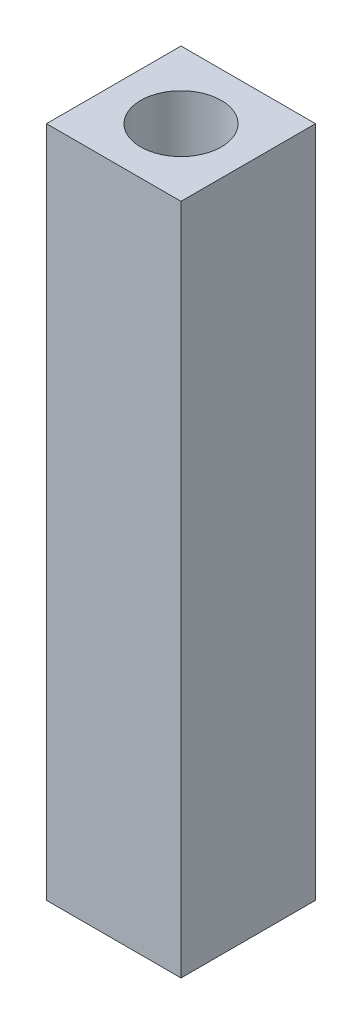
SolidWorks part; units mm, degrees
ref_plane "Front Plane" through (0, 0, 0) normal (0, 0, 1) x (1, 0, 0)
ref_plane "Top Plane" through (0, 0, 0) normal (0, 1, 0) x (1, 0, 0)
ref_plane "Right Plane" through (0, 0, 0) normal (1, 0, 0) x (0, 0, -1)
sketch "Sketch1" plane through (0, 0, 0) normal (0, 1, 0) x (1, 0, 0)
  line L1 (-5, 5) -> (5, 5)
  line L2 (-5, 5) -> (-5, -5)
  line L3 (-5, -5) -> (5, -5)
  line L4 (5, 5) -> (5, -5)
  line L5 (-5, 5) -> (5, -5) construction
  line L6 (-5, -5) -> (5, 5) construction
  dimension "D1" = 5
  dimension "D2" = 10
  dimension "D3" = 10
  dimension "D4" = 5
extrude "Boss-Extrude1" add sketch "Sketch1" along normal blind 50
sketch "Sketch2" plane through (0, 0, 0) normal (0, -1, 0) x (1, 0, 0)
  circle A0 centre (0, 0) radius 3
  dimension "D1" = 6
extrude "Cut-Extrude1" cut sketch "Sketch2" against normal blind 20
pattern_linear "LPattern1" count 2 spacing 30 along (0, 1, 0) of "Cut-Extrude1"
